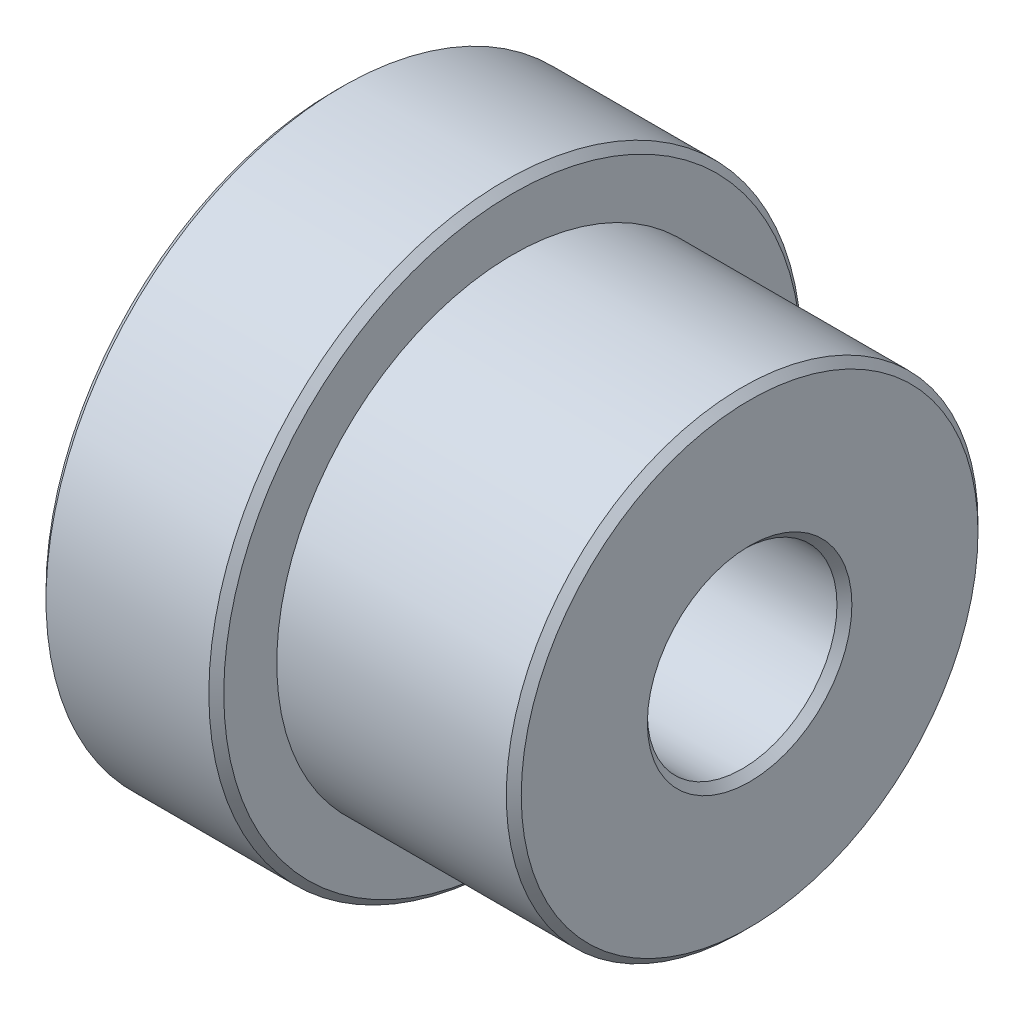
SolidWorks part; units mm, degrees
material "Nylon 101"
ref_plane "Front Plane" through (0, 0, 0) normal (0, 0, 1) x (1, 0, 0)
ref_plane "Top Plane" through (0, 0, 0) normal (0, 1, 0) x (1, 0, 0)
ref_plane "Right Plane" through (0, 0, 0) normal (1, 0, 0) x (0, 0, -1)
sketch "Sketch1" plane through (0, 0, 0) normal (1, 0, 0) x (0, 0, -1)
  circle A0 centre (0, 0) radius 12.6365
  dimension "D1" = 25.273
extrude "Boss-Extrude1" add sketch "Sketch1" along normal blind 12.7
sketch "Sketch2" plane through (0, 0, 0) normal (-1, 0, 0) x (0, 0, 1)
  circle A0 centre (0, 0) radius 15.875
  dimension "D1" = 31.75
extrude "Boss-Extrude2" add sketch "Sketch2" along normal blind 9.525
sketch "Sketch3" plane through (-9.525, 0, 0) normal (-1, 0, 0) x (0, 0, 1)
  circle A0 centre (0, 0) radius 11.1125
  dimension "D1" = 22.225
extrude "Cut-Extrude1" cut sketch "Sketch3" against normal blind 7.112
sketch "Sketch4" plane through (-2.413, 0, 0) normal (-1, 0, 0) x (0, 0, 1)
  circle A0 centre (0, 0) radius 7.2746
  dimension "D1" = 14.5492
extrude "Cut-Extrude2" cut sketch "Sketch4" against normal blind 0.2
sketch "Sketch5" plane through (-2.213, 0, 0) normal (-1, 0, 0) x (0, 0, 1)
  circle A0 centre (0, 0) radius 5.08
  dimension "D1" = 10.16
extrude "Cut-Extrude3" cut sketch "Sketch5" against normal through all
chamfer "Chamfer1" distance 0.4 angle 45 5 edges at (12.7, 0, -12.6365) (12.7, 0, 5.08) (-9.525, 0, 15.875) (-9.525, 0, 11.1125) (0, 0, 15.875)
